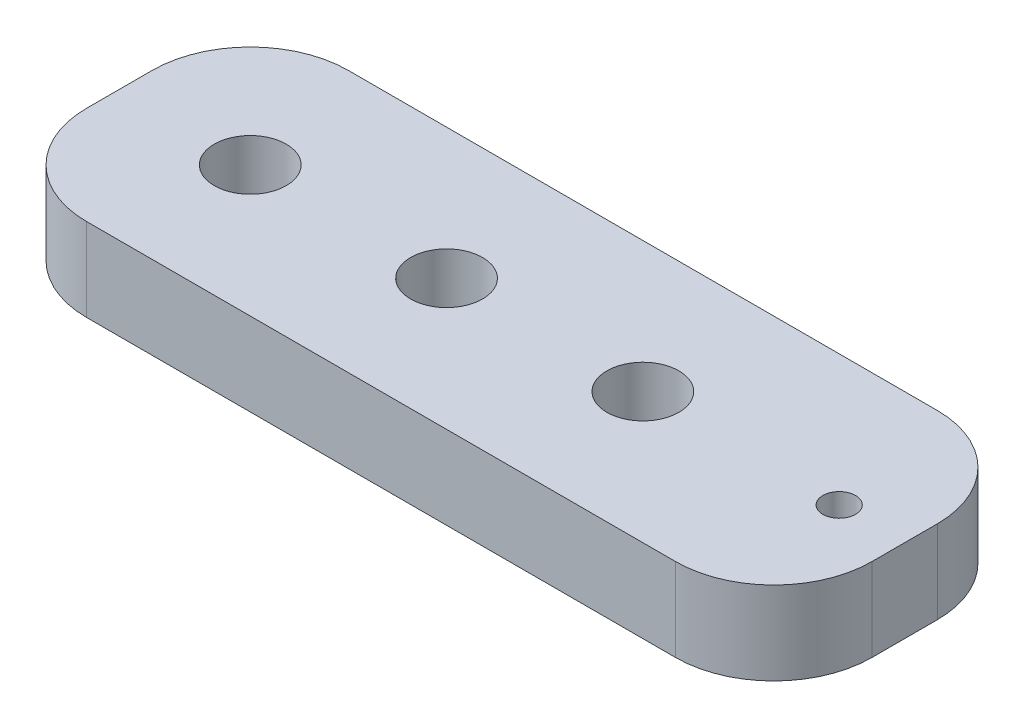
SolidWorks part; units mm, degrees
ref_plane "Front Plane" through (0, 0, 0) normal (0, 0, 1) x (1, 0, 0)
ref_plane "Top Plane" through (0, 0, 0) normal (0, 1, 0) x (1, 0, 0)
ref_plane "Right Plane" through (0, 0, 0) normal (1, 0, 0) x (0, 0, -1)
sketch "Sketch2" plane through (0, 0, 0) normal (0, 1, 0) x (1, 0, 0)
  line L1 (0, 0) -> (60, 0)
  line L2 (0, 0) -> (0, 20)
  line L3 (0, 20) -> (60, 20)
  line L4 (60, 0) -> (60, 20)
  dimension "D1" = 20
  dimension "D2" = 60
extrude "Boss-Extrude1" add sketch "Sketch2" along normal blind 6.35
sketch "Sketch6" plane through (0, 6.35, 0) normal (0, 1, 0) x (1, 0, 0)
  line L0 (0, 10) -> (60, 10) construction
  line L1 (0, 20) -> (0, 0) construction
  line L2 (60, 0) -> (60, 20) construction
  line L3 (60, 20) -> (0, 20) construction
  line L5 (5, 5) -> (5, 15)
  line L7 (11.35, 5) -> (11.35, 15)
  arc A0 (5, 15) -> (11.35, 15) centre (8.175, 15) cw
  arc A1 (5, 5) -> (11.35, 5) centre (8.175, 5) ccw
  point P12 (11.35, 10)
  point P13 (5, 10)
  dimension "D1" = 5
  dimension "D2" = 6.35
  dimension "D3" = 5
extrude "Cut-Extrude1" [suppressed] cut sketch "Sketch6" against normal through all
pattern_linear "LPattern1" [suppressed] count 2 spacing 20
hole_wizard "M5 Clearance Hole1" positions "3DSketch1" profile "Sketch4" hole size "M5" standard "ANSI Metric" end condition through all
sketch3d "3DSketch1"
  line L0 (0, 6.35, -10) -> (60, 6.35, -10) construction
  line L1 (0, 6.35, -20) -> (0, 6.35, 0) construction
  line L2 (60, 6.35, 0) -> (60, 6.35, -20) construction
  point P7 (10, 6.35, -10)
  point P9 (25, 6.35, -10)
  point P10 (40, 6.35, -10)
  dimension "D1" = 10
  dimension "D2" = 15
  dimension "D3" = 15
sketch "Sketch4" plane through (10, 6.35, -10) normal (1, 0, 0) x (0, 0, 1)
  line L0 (0, 0) -> (0, 6.35)
  line L1 (0, 6.35) -> (2.75, 6.35)
  line L2 (2.75, 6.35) -> (2.75, 0)
  line L5 (2.75, 0) -> (0, 0)
  line L11 (0, -6.35) -> (0, 107.95) construction
  dimension "Thru Hole Dia." = 5.5
  dimension "Thru Hole Depth" = 6.35
hole_wizard "Tap Drill for M3x0.5 Tap1" positions "3DSketch2" profile "Sketch5" hole size "M3x0.5" standard "ANSI Metric"
sketch3d "3DSketch2"
  line L0 (60, 6.35, -10) -> (0, 6.35, -10) construction
  line L1 (60, 6.35, 0) -> (60, 6.35, -20) construction
  line L4 (0, 0, -20) -> (0, 0, 0) construction
  line L5 (0, 6.35, -20) -> (0, 6.35, 0) construction
  point P0 (55, 6.35, -10)
  point P13 (0, 0, -10)
  dimension "D1" = 5
sketch "Sketch5" plane through (55, 6.35, -10) normal (1, 0, 0) x (0, 0, 1)
  line L0 (0, 0) -> (0, 6.35)
  line L1 (0, 6.35) -> (1.25, 6.35)
  line L2 (1.25, 6.35) -> (1.25, 0)
  line L5 (1.25, 0) -> (0, 0)
  line L11 (0, -6.35) -> (0, 107.95) construction
  dimension "Thru Hole Dia." = 2.5
  dimension "Thru Hole Depth" = 6.35
fillet "Fillet1" radius 7.5 4 edges at (60, 3.175, 0) (60, 3.175, -20) (0, 3.175, -20) (0, 3.175, 0)
